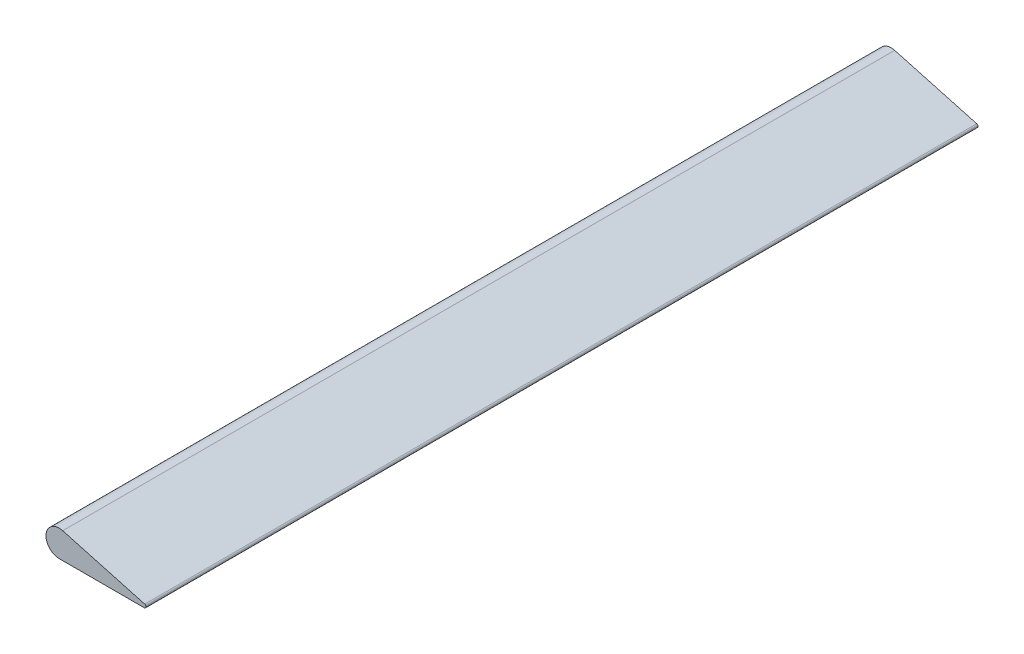
SolidWorks part; units mm, degrees
material "ABS"
ref_plane "Front Plane" through (0, 0, 0) normal (0, 0, 1) x (1, 0, 0)
ref_plane "Top Plane" through (0, 0, 0) normal (0, 1, 0) x (1, 0, 0)
ref_plane "Right Plane" through (0, 0, 0) normal (1, 0, 0) x (0, 0, -1)
sketch "Sketch2" plane through (0, 0, -3) normal (0, 0, 1) x (1, 0, 0)
  line L0 (442.7178, 24.3712) -> (474.4331, 20.1125) construction
  line L1 (442.557, 28.8563) -> (474.4331, 20.1125) construction
  line L4 (446.392, 20.1125) -> (474.4331, 20.1125)
  line L5 (474.4331, 20.1125) -> (447.3909, 27.5303)
  line L6 (474.4331, 20.1125) -> (441.3938, 20.1125) construction
  arc A1 (447.3909, 27.5303) -> (446.392, 20.1125) centre (446.392, 23.8886) ccw
extrude "Boss-Extrude1" add sketch "Sketch2" along normal blind 238
sketch "Sketch3" plane through (0, -30.5897, 0) normal (0, -1, 0) x (1, 0, 0)
  line L0 (442.6158, 235) -> (442.6158, -3) construction
  line L1 (442.6158, 190) -> (457.6158, 190)
  line L2 (442.6158, 190) -> (442.6158, 175)
  line L3 (442.6158, 175) -> (457.6158, 175)
  line L4 (457.6158, 190) -> (457.6158, 175)
  line L5 (446.392, -3) -> (474.4331, -3) construction
  line L6 (442.6158, 42) -> (457.6158, 42)
  line L7 (442.6158, 42) -> (442.6158, 57)
  line L8 (442.6158, 57) -> (457.6158, 57)
  line L9 (457.6158, 42) -> (457.6158, 57)
  line L10 (446.392, 235) -> (474.4331, 235) construction
  dimension "D1" = 15
  dimension "D2" = 15
  dimension "D3" = 45
  dimension "D4" = 15
  dimension "D5" = 15
  dimension "D6" = 45
extrude "Cut-Extrude1" cut sketch "Sketch3" against normal blind 54
fillet "Fillet1" radius 0.5 1 edges at (474.4331, 20.1125, 116)
fillet "Fillet2" radius 3 4 edges at (457.6158, 21.7614, 175) (457.6158, 21.7614, 190) (457.6158, 21.7614, 57) (457.6158, 21.7614, 42)
